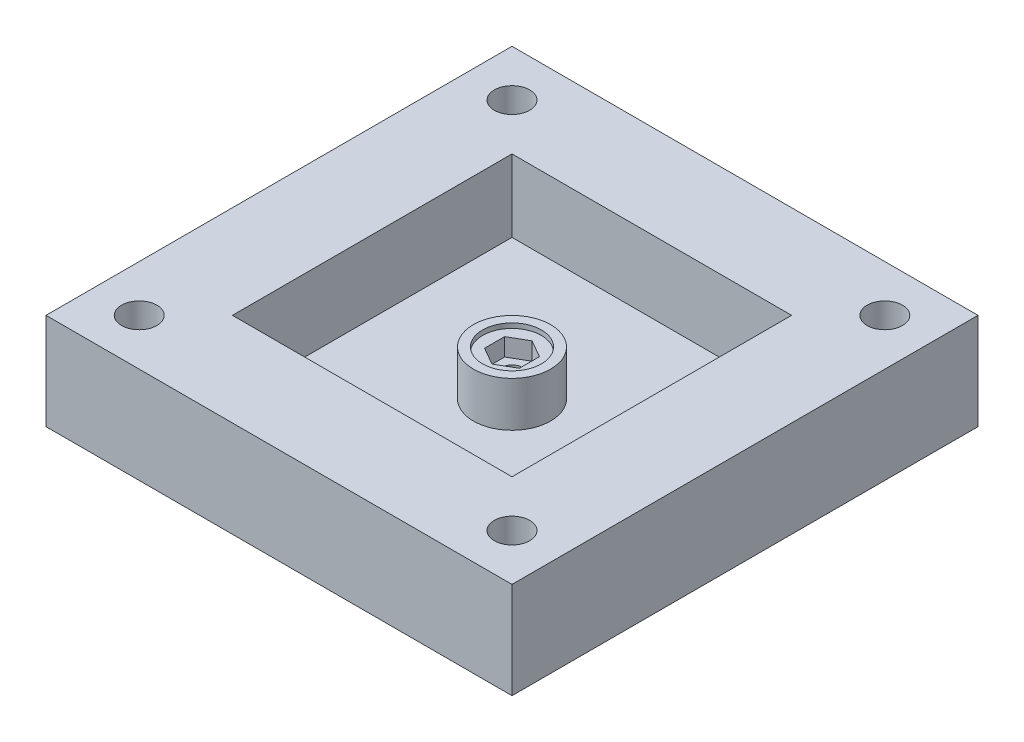
SolidWorks part; units mm, degrees
ref_plane "Front Plane" through (0, 0, 0) normal (0, 0, 1) x (1, 0, 0)
ref_plane "Top Plane" through (0, 0, 0) normal (0, 1, 0) x (1, 0, 0)
ref_plane "Right Plane" through (0, 0, 0) normal (1, 0, 0) x (0, 0, -1)
sketch "Sketch1" plane through (0, 0, 0) normal (0, 1, 0) x (1, 0, 0)
  line L1 (-72.5, -72.5) -> (72.5, -72.5)
  line L2 (-72.5, -72.5) -> (-72.5, 72.5)
  line L3 (-72.5, 72.5) -> (72.5, 72.5)
  line L4 (72.5, -72.5) -> (72.5, 72.5)
  line L5 (-72.5, -72.5) -> (72.5, 72.5) construction
  line L6 (-72.5, 72.5) -> (72.5, -72.5) construction
  point P0 (0, 0)
  dimension "D1" = 145
  dimension "D2" = 145
extrude "Boss-Extrude1" add sketch "Sketch1" along normal blind 30
sketch "Sketch2" plane through (0, 30, 0) normal (0, 1, 0) x (1, 0, 0)
  line L1 (-43.5, -43.5) -> (43.5, -43.5)
  line L2 (-43.5, -43.5) -> (-43.5, 43.5)
  line L3 (-43.5, 43.5) -> (43.5, 43.5)
  line L4 (43.5, -43.5) -> (43.5, 43.5)
  line L5 (-43.5, -43.5) -> (43.5, 43.5) construction
  line L6 (-43.5, 43.5) -> (43.5, -43.5) construction
  point P0 (0, 0)
  dimension "D1" = 87
  dimension "D2" = 87
extrude "Cut-Extrude1" cut sketch "Sketch2" against normal blind 22.5
sketch "Sketch3" plane through (0, 7.5, 0) normal (0, 1, 0) x (1, 0, 0)
  circle A0 centre (0, 0) radius 12
  dimension "D1" = 24
extrude "Boss-Extrude2" add sketch "Sketch3" along normal blind 14
sketch "Sketch4" plane through (0, 21.5, 0) normal (0, 1, 0) x (1, 0, 0)
  line L0 (0, 8.0403) -> (0, -8.6163) construction
  line L1 (0, 6.25) -> (-5.4127, 3.125)
  line L2 (-5.4127, 3.125) -> (-5.4127, -3.125)
  line L3 (-5.4127, -3.125) -> (0, -6.25)
  line L4 (0, -6.25) -> (5.4127, -3.125)
  line L5 (5.4127, -3.125) -> (5.4127, 3.125)
  line L6 (5.4127, 3.125) -> (0, 6.25)
  circle A0 centre (0, 0) radius 6.25 construction
  circle A1 centre (0, 0) radius 5.4127 construction
  dimension "D1" = 12.5
  dimension "D2" = 10.8253
extrude "Cut-Extrude2" cut sketch "Sketch4" against normal blind 7
sketch "Sketch5" plane through (0, 30, 0) normal (0, 1, 0) x (1, 0, 0)
  line L0 (0, -16.5) -> (0, 16.5) construction
  line L1 (-63.25, 52.75) -> (-52.75, 52.75) construction
  line L2 (-63.25, 52.75) -> (-63.25, 63.25) construction
  line L3 (-58, 66.8031) -> (-58, 49.1969) construction
  line L4 (-72.5, 72.5) -> (-72.5, -72.5) construction
  line L5 (-43.5, 43.5) -> (-43.5, -43.5) construction
  line L6 (-74.6062, 58) -> (-57, 58) construction
  line L7 (72.5, 72.5) -> (-72.5, 72.5) construction
  line L8 (43.5, 43.5) -> (-43.5, 43.5) construction
  line L10 (-63.25, 63.25) -> (-52.75, 63.25) construction
  line L12 (-52.75, 52.75) -> (-52.75, 63.25) construction
  line L13 (-63.25, 52.75) -> (-52.75, 63.25) construction
  line L14 (-63.25, 63.25) -> (-52.75, 52.75) construction
  line L15 (63.25, 63.25) -> (52.75, 63.25) construction
  line L16 (52.75, 52.75) -> (52.75, 63.25) construction
  line L17 (63.25, 52.75) -> (52.75, 52.75) construction
  line L18 (63.25, 52.75) -> (63.25, 63.25) construction
  line L19 (-16.5, 0) -> (16.5, 0) construction
  line L20 (63.25, -52.75) -> (63.25, -63.25) construction
  line L21 (63.25, -52.75) -> (52.75, -52.75) construction
  line L22 (52.75, -52.75) -> (52.75, -63.25) construction
  line L23 (63.25, -63.25) -> (52.75, -63.25) construction
  line L24 (-63.25, -63.25) -> (-52.75, -63.25) construction
  line L25 (-52.75, -52.75) -> (-52.75, -63.25) construction
  line L26 (-63.25, -52.75) -> (-52.75, -52.75) construction
  line L27 (-63.25, -52.75) -> (-63.25, -63.25) construction
  circle A4 centre (-58, 58) radius 5.5
  circle A5 centre (58, 58) radius 5.5
  circle A6 centre (58, -58) radius 5.5
  circle A7 centre (-58, -58) radius 5.5
  point P0 (-58, 58)
  dimension "D1" = 10.5
  dimension "D2" = 11
extrude "Cut-Extrude3" cut sketch "Sketch5" against normal blind 15
sketch "Sketch6" plane through (0, 14.5, 0) normal (0, 1, 0) x (1, 0, 0)
  circle A0 centre (0, 0) radius 3.05
  dimension "D1" = 6.1
extrude "Cut-Extrude4" cut sketch "Sketch6" against normal up to next
sketch "Sketch7" plane through (0, 21.5, 0) normal (0, 1, 0) x (1, 0, 0)
  circle A0 centre (0, 0) radius 9.15
  dimension "D1" = 18.3
extrude "Cut-Extrude5" cut sketch "Sketch7" against normal blind 1.5
